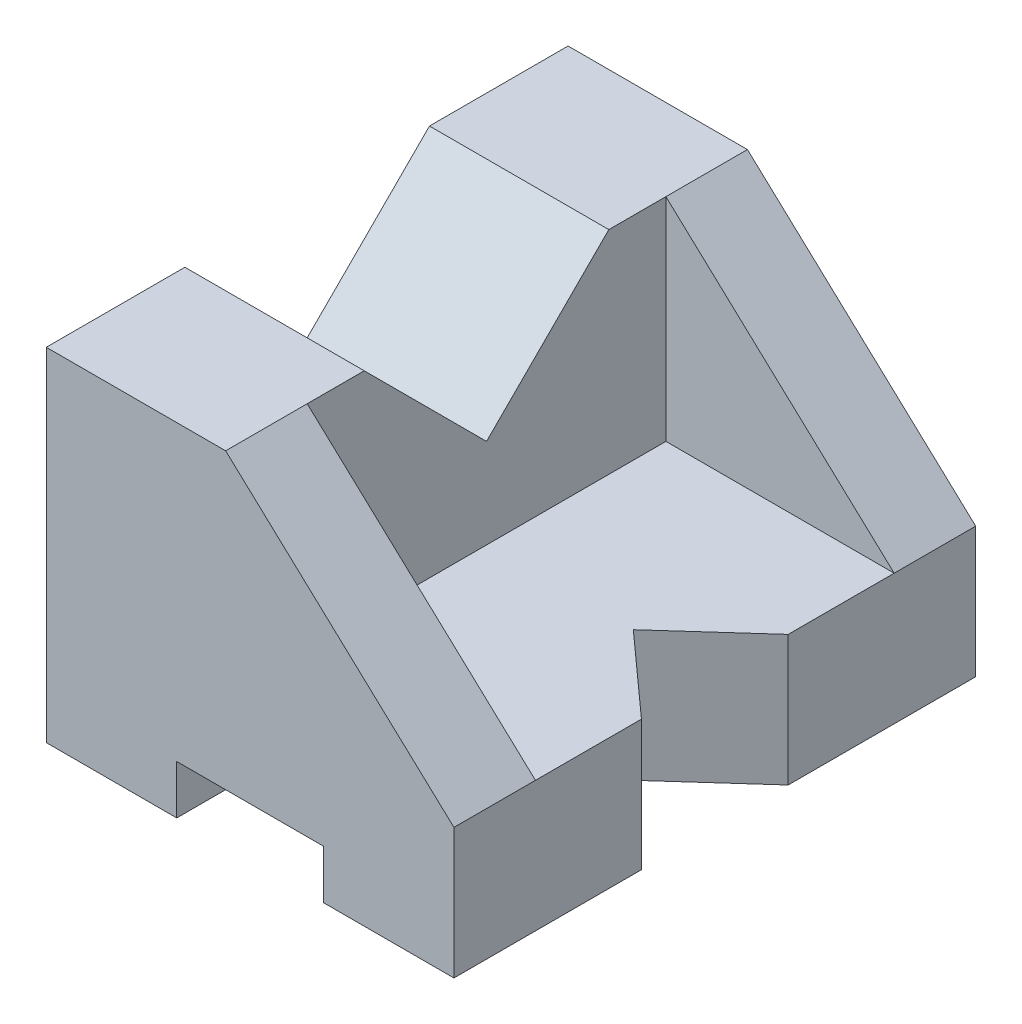
SolidWorks part; units mm, degrees
ref_plane "Front Plane" through (0, 0, 0) normal (0, 0, 1) x (1, 0, 0)
ref_plane "Top Plane" through (0, 0, 0) normal (0, 1, 0) x (1, 0, 0)
ref_plane "Right Plane" through (0, 0, 0) normal (1, 0, 0) x (0, 0, -1)
sketch "Sketch1" plane through (0, 0, 0) normal (0, 0, 1) x (1, 0, 0)
  line L0 (0, 0) -> (0, 42)
  line L1 (0, 42) -> (22, 42)
  line L2 (22, 42) -> (50, 16)
  line L3 (50, 16) -> (50, 0)
  line L4 (50, 0) -> (34, 0)
  line L5 (34, 0) -> (34, 6)
  line L6 (34, 6) -> (16, 6)
  line L7 (16, 6) -> (16, 0)
  line L8 (16, 0) -> (0, 0)
  dimension "D1" = 42
  dimension "D2" = 22
  dimension "D3" = 16
  dimension "D4" = 16
  dimension "D5" = 6
  dimension "D6" = 16
  dimension "D7" = 50
extrude "Boss-Extrude2" add sketch "Sketch1" against normal blind 64
sketch "Sketch3" plane through (0, 42, 0) normal (0, 1, 0) x (1, 0, 0)
  line L0 (22, 64) -> (22, 0) construction
  line L1 (22, 54) -> (50, 54)
  line L2 (22, 54) -> (22, 10)
  line L3 (22, 10) -> (50, 10)
  line L4 (50, 54) -> (50, 10)
  line L5 (50, 64) -> (50, 0) construction
  point P8 (22, 32)
  point P9 (22, 32)
  dimension "D1" = 44
extrude "Cut-Extrude3" cut sketch "Sketch3" against normal blind 26 contours L2 L1 L4 L3
sketch "Sketch5" plane through (22, 0, 0) normal (1, 0, 0) x (0, 0, -1)
  line L1 (54, 42) -> (10, 42) construction
  line L2 (32, 27) -> (47, 42)
  line L3 (47, 42) -> (17, 42)
  line L4 (17, 42) -> (32, 27)
  point P4 (32, 42)
  dimension "D2" = 30
extrude "Cut-Extrude4" cut sketch "Sketch5" against normal through all
sketch "Sketch7" plane through (0, 16, 0) normal (0, 1, 0) x (1, 0, 0)
  line L1 (50, 54) -> (50, 10) construction
  line L2 (40, 32) -> (50, 41)
  line L3 (50, 41) -> (50, 23)
  line L4 (50, 23) -> (40, 32)
  point P4 (50, 32)
extrude "Cut-Extrude6" cut sketch "Sketch7" against normal through all
